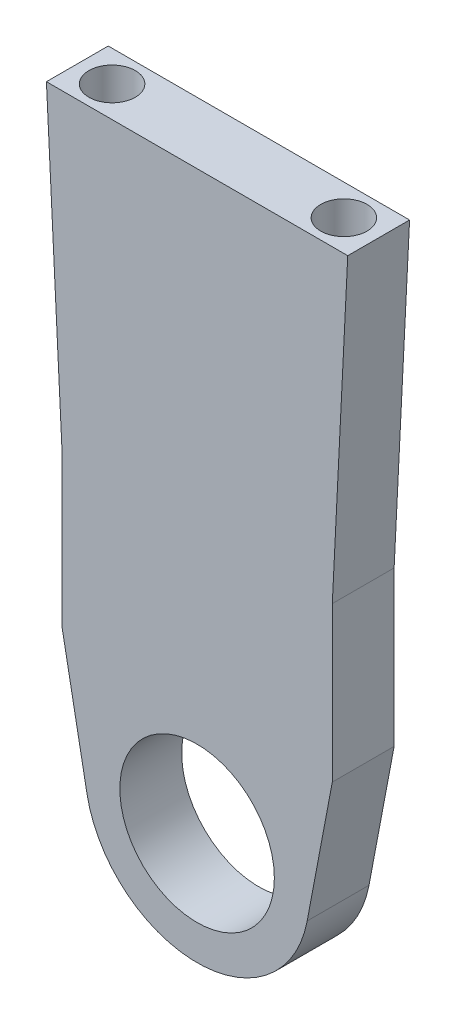
SolidWorks part; units mm, degrees
material "6063-T1"
ref_plane "Front Plane" through (0, 0, 0) normal (0, 0, 1) x (1, 0, 0)
ref_plane "Top Plane" through (0, 0, 0) normal (0, 1, 0) x (1, 0, 0)
ref_plane "Right Plane" through (0, 0, 0) normal (1, 0, 0) x (0, 0, -1)
sketch "Sketch1" plane through (0, 0, 0) normal (0, 0, 1) x (1, 0, 0)
  line L0 (8.75, 7.25) -> (-8.75, 7.25)
  line L1 (8.75, 7.25) -> (7.1237, -1.3475)
  line L2 (-8.75, 7.25) -> (-7.1237, -1.3475)
  line L4 (0, -2.2) -> (0, 2.2) construction
  arc A0 (7.1237, -1.3475) -> (-7.1237, -1.3475) centre (0, 0) cw
  circle A1 centre (0, 0) radius 5
  dimension "D4" = 10
  dimension "D5" = 7.25
  dimension "D1" = 17.5
  dimension "D2" = 7.25
  dimension "D3" = 8.75
extrude "Boss-Extrude1" add sketch "Sketch1" along normal mid plane 4
sketch "Sketch2" plane through (0, 7.25, 0) normal (0, 1, 0) x (1, 0, 0)
  line L1 (-8.75, 2) -> (8.75, 2)
  line L2 (-8.75, 2) -> (-8.75, -2)
  line L3 (-8.75, -2) -> (8.75, -2)
  line L4 (8.75, 2) -> (8.75, -2)
extrude "Boss-Extrude2" add sketch "Sketch2" along normal blind 30
sketch "Sketch3" plane through (0, 37.25, 0) normal (0, 1, 0) x (1, 0, 0)
  line L0 (-12.1, 0) -> (12.1, 0) construction
  line L1 (0, -2.2) -> (0, 2.2) construction
  circle A0 centre (-7.5, 0) radius 1.5
  circle A1 centre (7.5, 0) radius 1.5
  dimension "D1" = 3
  dimension "D2" = 15
  dimension "D3" = 7.5
sketch "Sketch4" plane through (0, 0, 0) normal (0, 0, 1) x (1, 0, 0)
  line L0 (-8.75, 37.25) -> (-9.75, 37.25)
  line L1 (-9.75, 37.25) -> (-8.75, 17.25)
  line L2 (-8.75, 37.25) -> (-8.75, 7.25) construction
  line L3 (8.75, 37.25) -> (9.75, 37.25)
  line L4 (9.75, 37.25) -> (8.75, 17.25)
  line L5 (8.75, 37.25) -> (8.75, 7.25) construction
  line L6 (8.75, 17.25) -> (8.75, 37.25)
  line L7 (-8.75, 37.25) -> (-8.75, 17.25)
  dimension "D1" = 1
  dimension "D2" = 20
extrude "Boss-Extrude3" add sketch "Sketch4" along normal mid plane 4
extrude "Cut-Extrude1" cut sketch "Sketch3" against normal blind 6
equation "\"OuterRad\"= 14.5 / 2"
equation "\"D5@Sketch1\"=\"OuterRad\""
equation "\"D2@Sketch1\"=\"OuterRad\""
equation "\"InnerDiameter\" = 10"
equation "\"D4@Sketch1\"=\"InnerDiameter\""
equation "\"Thick\"=4.000000"
equation "\"D1@Boss-Extrude1\"=\"Thick\""
equation "\"ScrewDiam\"= 3"
equation "\"ScrewDist\"=15"
equation "\"D1@Boss-Extrude3\"=\"Thick\""
equation "\"FlangeXDist\"=1.000000"
equation "\"D1@Sketch4\"=\"FlangeXDist\""
equation "\"D1@Sketch3\"=\"ScrewDiam\""
equation "\"D2@Sketch3\"=\"ScrewDist\""
equation "\"D3@Sketch3\"=\"ScrewDist\"/2"
